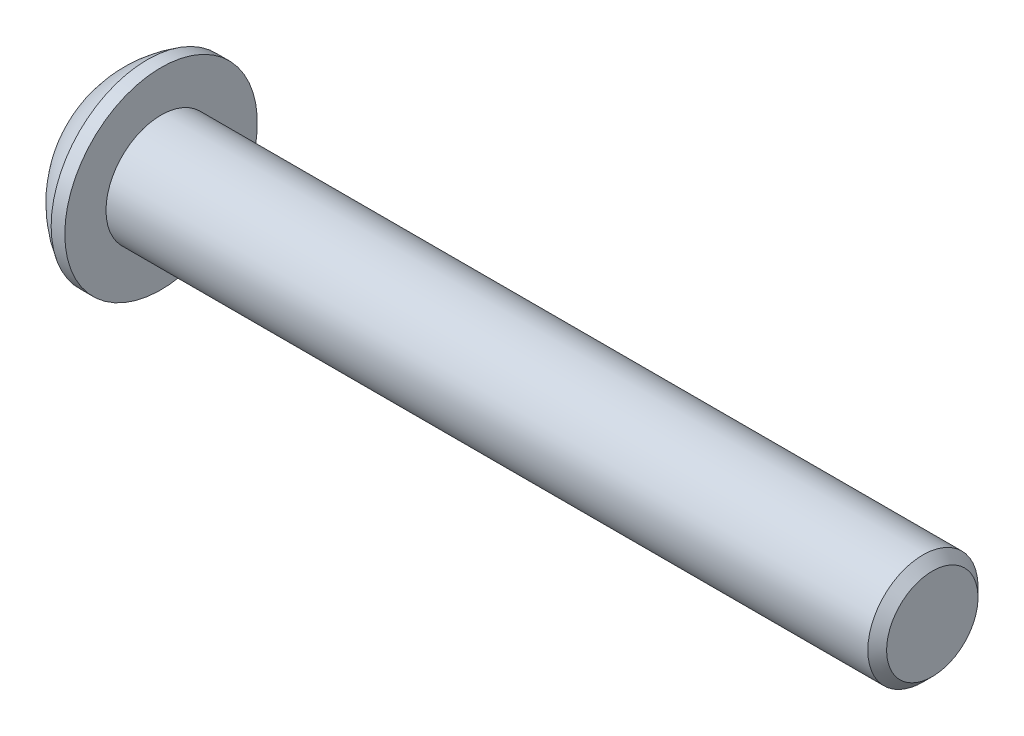
SolidWorks part; units mm, degrees
ref_plane "Plane1" through (0, 0, 0) normal (0, 0, 1) x (1, 0, 0)
ref_plane "Plane2" through (0, 0, 0) normal (0, 1, 0) x (1, 0, 0)
ref_plane "Plane3" through (0, 0, 0) normal (1, 0, 0) x (0, 0, -1)
sketch "BodySke" plane through (0, 0, 0) normal (0, 0, 1) x (1, 0, 0)
  line L0 (47.8028, 0) -> (47.8028, 2.634)
  line L1 (47.2618, 3.175) -> (3.3528, 3.175)
  line L2 (3.3528, 3.175) -> (3.3528, 5.5499)
  line L3 (3.3528, 5.5499) -> (2.5654, 5.5499)
  line L4 (0, 0) -> (101.6, 0) construction
  line L5 (3.3528, -5.5499) -> (2.5654, -5.5499) construction
  line L6 (55.6768, -3.175) -> (3.3528, -3.175) construction
  line L7 (47.8028, 0) -> (0, 0)
  line L8 (0, 2.775) -> (0, -2.775) construction
  line L9 (0, 0) -> (0, 2.775)
  line L10 (47.8028, 2.634) -> (47.2618, 3.175)
  line L11 (47.8028, -2.634) -> (47.2618, -3.175) construction
  line L12 (4.2596, 9.525) -> (4.2596, -3.175) construction
  line L13 (3.3528, 9.525) -> (3.3528, -3.175) construction
  arc A1 (0, 2.775) -> (2.5654, 5.5499) centre (5.7851, 0) cw
  dimension "Diameter" = 6.35
  dimension "Length" = 44.45
  dimension "Head_dia" = 11.0998
  dimension "D1" = 5.5499
  dimension "Head_ht" = 3.3528
  dimension "Head_side_ht" = 0.7874
  dimension "Minor_dia" = 5.268
  dimension "Body_ch_ang" = 45
  dimension "Advance" = 0.9068
  dimension "Thread_nom" = 44.45
revolve "BaseBody" add sketch "BodySke" angle 360 about L4
cosmetic thread "ThreadCosmetic" [suppressed] parameters "Thread_length"=43.5432, "Thread_minor"=5.268
sketch "Sketch2" plane through (0, 0, 0) normal (0, 0, 1) x (1, 0, 0)
  line L0 (0, 1.9812) -> (2.2098, 1.9812)
  line L1 (2.2098, 1.9812) -> (3.3536, 0)
  line L3 (3.3536, 0) -> (0, 0)
  line L4 (0, 0) -> (0, 1.9812)
  line L5 (0, -1.9812) -> (2.2098, -1.9812) construction
  line L6 (0, 0) -> (47.625, 0) construction
  dimension "D2" = 60
  dimension "PreBroach_depth" = 2.2098
  dimension "PreBroach_dia" = 3.9624
revolve "PreBroach" cut sketch "Sketch2" angle 360 about L6
sketch "Sketch3" plane through (0, 0, 0) normal (1, 0, 0) x (0, 0, -1)
  line L0 (-1.9812, -1.1438) -> (-1.9812, 1.1438)
  line L1 (-1.9812, 1.1438) -> (0, 2.2877)
  line L2 (0, 2.2877) -> (1.9812, 1.1438)
  line L3 (1.9812, 1.1438) -> (1.9812, -1.1438)
  line L4 (1.9812, -1.1438) -> (0, -2.2877)
  line L5 (0, -2.2877) -> (-1.9812, -1.1438)
  dimension "Hex_size" = 3.9624
  dimension "D3" = 3.9624
  dimension "D1" = 1.9812
  dimension "D2" = 1.9812
extrude "Hex" cut sketch "Sketch3" along normal blind 2.2098
sketch "Sketch4" plane through (0, 9.525, 0) normal (1, 0, 0) x (0, 0, -1)
  line L0 (0, -9.525) -> (2.3876, -9.525)
  line L1 (0, -9.525) -> (6.1484, -5.9752) construction
  line L2 (0, -9.525) -> (1.1938, -7.4573)
  line L3 (1.9883, -8.949) -> (2.2704, -8.7861)
  line L4 (1.493, -8.0911) -> (1.7751, -7.9282)
  arc A0 (1.9883, -8.949) -> (1.493, -8.0911) centre (0, -9.525) ccw
  arc A1 (2.3876, -9.525) -> (2.2704, -8.7861) centre (0, -9.525) ccw
  arc A2 (1.1938, -7.4573) -> (1.7751, -7.9282) centre (0, -9.525) cw
  dimension "Spline_n_dim" = 4.1402
  dimension "Spline_m_dim" = 4.7752
  dimension "D1" = 30
  dimension "D2" = 60
  dimension "Spline_p_dim" = 0.9906
  dimension "D3" = 0.4953
extrude "Spline" [suppressed] cut sketch "Sketch4" along normal blind 2.2098
pattern_circular "CirPattern1" [suppressed] count 6 every 60 about axis through (0, 0, 0) along (1, 0, 0)
sketch "ThdSchSke" plane through (0, 0, 0) normal (0, 0, 1) x (1, 0, 0)
  line L0 (4.2596, -2.634) -> (3.8808, -3.175)
  line L1 (4.2596, -2.634) -> (4.6384, -3.175)
  line L2 (4.6384, -3.175) -> (4.6384, -3.9688)
  line L3 (-3.175, 0) -> (5.1513, 0) construction
  line L5 (4.6384, -3.9688) -> (3.8808, -3.9688)
  line L6 (3.8808, -3.9688) -> (3.8808, -3.175)
  dimension "Diameter" = 6.35
  dimension "Thread_minor" = 5.268
  dimension "SideAngle" = 55
  dimension "VeeAngle" = 70
  dimension "Overcut" = 7.9375
  dimension "Start" = 4.2596
revolve "ThreadSchematic" [suppressed] cut sketch "ThdSchSke" angle 360 about L3
pattern_linear "ThdSchPat" [suppressed]
equation "\"D1@BodySke\" = \"Head_dia@BodySke\" * .5"
equation "\"Thread_minor@ThreadCosmetic\" = \"Minor_dia@BodySke\""
equation "\"D1@Sketch3\" = \"Hex_size@Sketch3\" / 2"
equation "\"D2@Sketch3\" = \"D1@Sketch3\""
equation "\"D3@Sketch3\" = \"Hex_size@Sketch3\""
equation "\"D3@Sketch4\" = \"Spline_p_dim@Sketch4\" / 2"
equation "\"D1@Sketch4\" = \"D2@Sketch4\" / 2"
equation "\"Thread_length@ThreadCosmetic\" = ((sgn( (\"Length@BodySke\" - \"Advance@BodySke\" ) - \"Thread_nom@BodySke\" )-1)*( (\"Length@BodySke\" - \"Advance@BodySke\" ) - \"Thread_nom@BodySke\" ))/-2+ \"Thread_nom@BodySke\""
equation "\"Thread_minor@ThdSchSke\" = \"Minor_dia@BodySke\""
equation "\"Diameter@ThdSchSke\" = \"Diameter@BodySke\""
equation "\"Overcut@ThdSchSke\" = \"Diameter@BodySke\" * 1.25"
equation "\"Start@ThdSchSke\" = \"Head_ht@BodySke\" + \"Length@BodySke\" - \"Thread_length@ThreadCosmetic\"  '---Non-countersunk---"
equation "\"Num_threads@ThdSchPat\" = int( \"Thread_length@ThreadCosmetic\" / \"Advance@BodySke\" + 0.999 )  + 1"
equation "\"Advance@ThdSchPat\" = \"Thread_length@ThreadCosmetic\" /  (\"Num_threads@ThdSchPat\" - 1) 'relax it"
equation "\"Num_threads@ThdSchPat\" = \"Num_threads@ThdSchPat\" - sgn( \"Num_threads@ThdSchPat\" - 1) '---chamfered tips only---"
